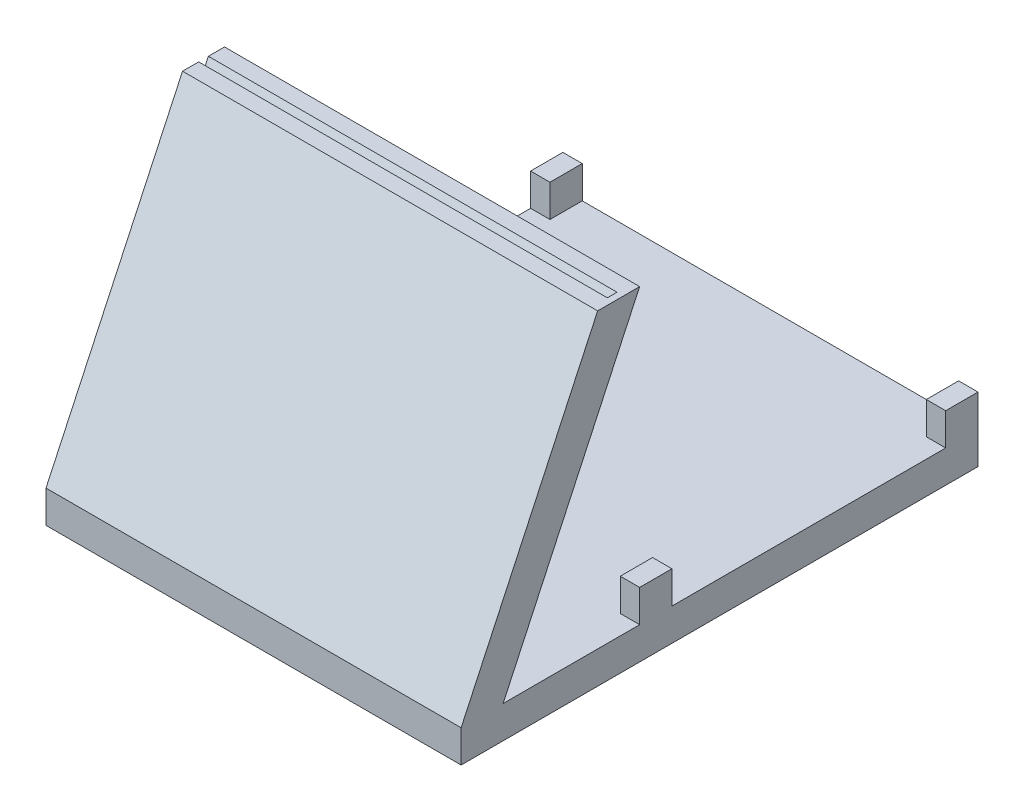
SolidWorks part; units mm, degrees
ref_plane "Front Plane" through (0, 0, 0) normal (0, 0, 1) x (1, 0, 0)
ref_plane "Top Plane" through (0, 0, 0) normal (0, 1, 0) x (1, 0, 0)
ref_plane "Right Plane" through (0, 0, 0) normal (1, 0, 0) x (0, 0, -1)
sketch "Sketch1" plane through (0, 0, 0) normal (0, 1, 0) x (1, 0, 0)
  line L1 (-64.25, -80) -> (64.25, -80)
  line L2 (-64.25, -80) -> (-64.25, 80)
  line L3 (-64.25, 80) -> (64.25, 80)
  line L4 (64.25, -80) -> (64.25, 80)
  line L5 (-64.25, -80) -> (64.25, 80) construction
  line L6 (-64.25, 80) -> (64.25, -80) construction
  point P0 (0, 0)
  dimension "D1" = 128.5
  dimension "D2" = 160
extrude "Boss-Extrude1" add sketch "Sketch1" along normal blind 10
sketch "Sketch2" plane through (0, 10, 0) normal (0, 1, 0) x (1, 0, 0)
  line L0 (-64.25, -80) -> (64.25, -80)
  line L1 (64.25, -80) -> (64.25, -67)
  line L2 (64.25, -80) -> (64.25, 80) construction
  line L3 (64.25, -67) -> (-64.25, -67)
  line L4 (-64.25, 80) -> (-64.25, -80) construction
  line L5 (-64.25, -67) -> (-64.25, -72)
  line L6 (-64.25, -72) -> (62.25, -72)
  line L7 (62.25, -72) -> (62.25, -75)
  line L8 (62.25, -75) -> (-64.25, -75)
  line L9 (-64.25, -75) -> (-64.25, -80)
  dimension "D1" = 5
  dimension "D2" = 3
  dimension "D3" = 2
sketch "Sketch4" plane through (64.25, 0, 0) normal (1, 0, 0) x (0, 0, -1)
  line L0 (-80, 10) -> (-37.7382, 100.6308)
  line L1 (-75, 10) -> (-80, 10) construction
  dimension "D1" = 65
  dimension "D2" = 100
sweep "Sweep1" add profiles "Sketch2" path "Sketch4"
sketch "Sketch6" plane through (0, 10, 0) normal (0, 1, 0) x (1, 0, 0)
  line L1 (-64.25, 80) -> (-58.25, 80)
  line L2 (-64.25, 80) -> (-64.25, 70)
  line L3 (-64.25, 70) -> (-58.25, 70)
  line L4 (-58.25, 80) -> (-58.25, 70)
  line L5 (-64.25, -24.7382) -> (-58.25, -24.7382)
  line L6 (-64.25, -24.7382) -> (-64.25, -14.7382)
  line L7 (-64.25, -14.7382) -> (-58.25, -14.7382)
  line L8 (-58.25, -24.7382) -> (-58.25, -14.7382)
  line L9 (64.25, 80) -> (58.25, 80)
  line L10 (64.25, 80) -> (64.25, 70)
  line L11 (64.25, 70) -> (58.25, 70)
  line L12 (58.25, 80) -> (58.25, 70)
  line L13 (64.25, -24.7382) -> (58.25, -24.7382)
  line L14 (64.25, -24.7382) -> (64.25, -14.7382)
  line L15 (64.25, -14.7382) -> (58.25, -14.7382)
  line L16 (58.25, -24.7382) -> (58.25, -14.7382)
  dimension "D1" = 6
  dimension "D2" = 10
extrude "Boss-Extrude2" add sketch "Sketch6" along normal blind 10
